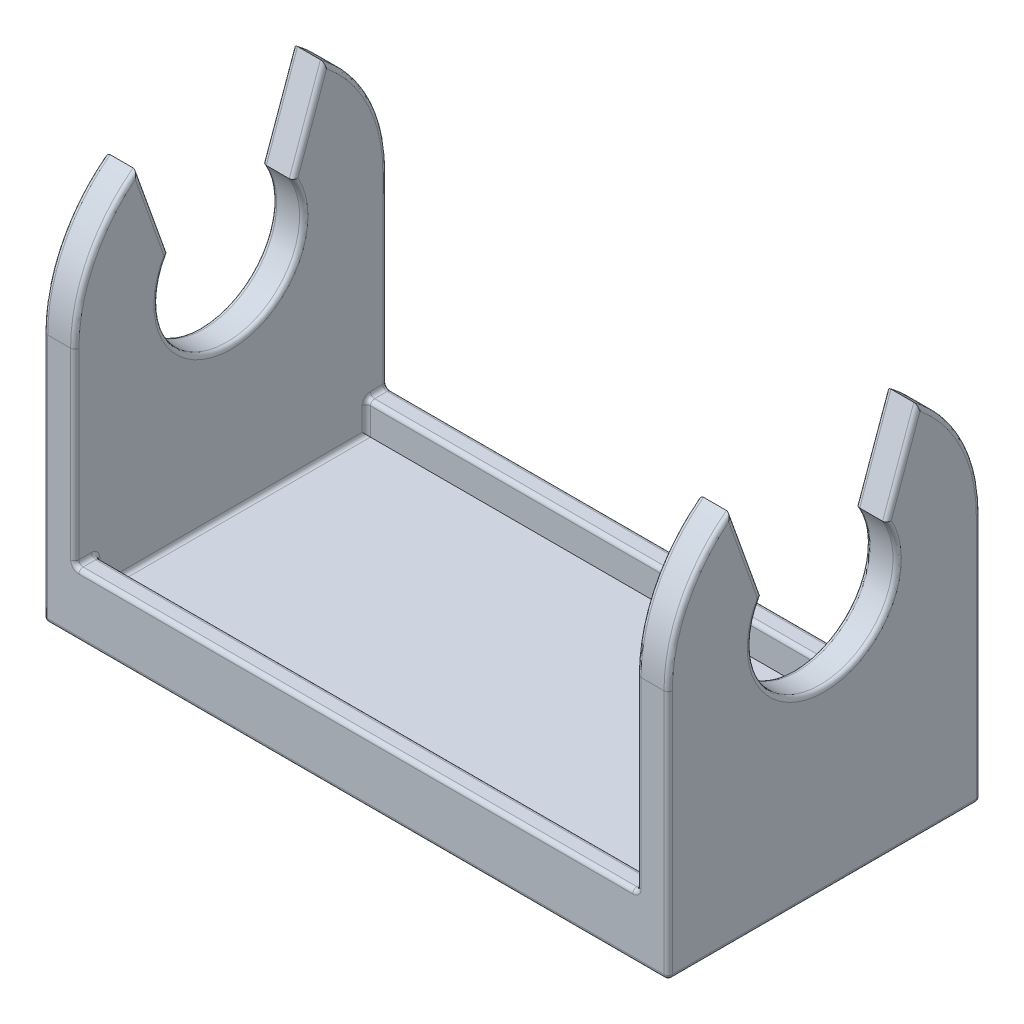
SolidWorks part; units mm, degrees
ref_plane "前视基准面" through (0, 0, 0) normal (0, 0, 1) x (1, 0, 0)
ref_plane "上视基准面" through (0, 0, 0) normal (0, 1, 0) x (1, 0, 0)
ref_plane "右视基准面" through (0, 0, 0) normal (1, 0, 0) x (0, 0, -1)
sketch "草图1" plane through (0, 0, 0) normal (1, 0, 0) x (0, 0, -1)
  line L0 (0, 0) -> (0, 12) construction
  line L1 (7.5, 0) -> (-7.5, 0)
  line L6 (-7.5, 0) -> (-7.5, 12)
  line L7 (0, 12) -> (-3, 12) construction
  line L8 (-3, 12) -> (-3, 13.8028) construction
  line L9 (0, 12) -> (-4.5, 12) construction
  line L10 (-4.5, 12) -> (-4.5, 18) construction
  line L11 (-4.5, 18) -> (-3, 13.8028)
  line L16 (7.5, 0) -> (7.5, 12)
  line L17 (4.5, 18) -> (3, 13.8028)
  arc A0 (-3, 13.8028) -> (3, 13.8028) centre (0, 12) ccw
  arc A1 (-4.5, 18) -> (-7.5, 12) centre (0, 12) ccw
  arc A2 (4.5, 18) -> (7.5, 12) centre (0, 12) cw
  dimension "D2" = 7
  dimension "D8" = 15
  dimension "D1" = 12
  dimension "D3" = 7.5
  dimension "D9" = 3
  dimension "D10" = 4.5
  dimension "D11" = 90
extrude "凸台-拉伸1" add sketch "草图1" along normal blind 30
sketch "草图2" plane through (0, 0, 7.5) normal (0, 0, 1) x (1, 0, 0)
  line L0 (30, 18) -> (0, 18) construction
  line L1 (1.5, 1.5) -> (28.5, 1.5)
  line L2 (1.5, 1.5) -> (1.5, 18)
  line L3 (1.5, 18) -> (28.5, 18)
  line L4 (28.5, 1.5) -> (28.5, 18)
  line L5 (0, 12) -> (0, 0) construction
  line L6 (30, 0) -> (0, 0) construction
  line L7 (30, 12) -> (30, 0) construction
  dimension "D1" = 1.5
  dimension "D2" = 1.5
  dimension "D3" = 1.5
extrude "切除-拉伸1" cut sketch "草图2" against normal up to next
sketch "草图3" plane through (0, 1.5, 0) normal (0, 1, 0) x (1, 0, 0)
  line L0 (28.5, 7.5) -> (28.5, 4.5) construction
  line L1 (1.5, 7.5) -> (28.5, 7.5)
  line L2 (1.5, 7.5) -> (1.5, 6.5)
  line L3 (1.5, 6.5) -> (28.5, 6.5)
  line L4 (28.5, 7.5) -> (28.5, 6.5)
  line L5 (28.5, 7.5) -> (28.5, -7.5) construction
  line L6 (1.5, -7.5) -> (28.5, -7.5)
  line L7 (1.5, -7.5) -> (1.5, -6.5)
  line L8 (1.5, -6.5) -> (28.5, -6.5)
  line L9 (28.5, -7.5) -> (28.5, -6.5)
  dimension "D1" = 1
  dimension "D2" = 1
extrude "凸台-拉伸2" add sketch "草图3" along normal blind 1.5
sketch "草图4" plane through (0, 0, 0) normal (0, 0, 1) x (1, 0, 0)
  line L0 (0, 0) -> (7.5, 0) construction
  line L1 (30, 0) -> (0, 0) construction
  line L2 (7.5, 0) -> (7.5, -2) construction
  line L3 (7.5, -2) -> (7.5, -2.5) construction
  line L4 (6, 0) -> (9, 0)
  line L5 (9, 0) -> (9, -0.6771)
  line L6 (5.55, -2.5) -> (9.45, -2.5)
  line L7 (9.45, -2.5) -> (9.45, -1.5556)
  line L8 (5.55, -2.5) -> (5.55, -1.5556)
  line L9 (6, 0) -> (6, -0.6771)
  arc A0 (9.45, -1.5556) -> (9, -0.6771) centre (7.5, -2) ccw
  arc A1 (5.55, -1.5556) -> (6, -0.6771) centre (7.5, -2) cw
  dimension "D6" = 2
  dimension "D1" = 7.5
  dimension "D2" = 2
  dimension "D3" = 0.5
  dimension "D4" = 1.5
  dimension "D5" = 1.95
extrude "凸台-拉伸3" add sketch "草图4" along normal blind 2 and the other way blind 2
pattern_linear "阵列(线性)1" count 2 spacing 15 along (1, 0, 0) of "凸台-拉伸3"
sketch "草图5" plane through (0, 0, 0) normal (-1, 0, 0) x (0, 0, 1)
  line L0 (0, 0) -> (0, -2) construction
  line L1 (0, -2) -> (0, -2.5) construction
  line L2 (-2, -2.5) -> (2, -2.5) construction
  line L3 (0, 0) -> (1.5, 0) construction
  line L4 (7.5, 0) -> (-7.5, 0) construction
  line L5 (1.5, 0) -> (1.5, -0.6771)
  line L6 (0, -2.5) -> (1.95, -2.5) construction
  line L7 (1.95, -2.5) -> (1.95, -1.5556)
  line L8 (1.95, -2.5) -> (2, -2.5)
  line L9 (2, -2.5) -> (2, 0)
  line L10 (2, 0) -> (1.5, 0)
  line L11 (-2, 0) -> (-1.5, 0)
  line L12 (-2, -2.5) -> (-2, 0)
  line L13 (-1.95, -2.5) -> (-2, -2.5)
  line L14 (-1.95, -2.5) -> (-1.95, -1.5556)
  line L15 (-1.5, 0) -> (-1.5, -0.6771)
  arc A0 (1.95, -1.5556) -> (1.5, -0.6771) centre (0, -2) ccw
  arc A1 (-1.95, -1.5556) -> (-1.5, -0.6771) centre (0, -2) cw
  dimension "D1" = 2
  dimension "D2" = 1.5
  dimension "D3" = 1.95
extrude "切除-拉伸2" cut sketch "草图5" against normal through all
fillet "圆角1" radius 0.2 46 edges at (28.5, 1.5, 0) (28.5, 2.25, -6.5) (28.5, 15.3541, -6.7082) (28.5, 15.9014, -3.75) (28.5, 8.5, 0) (28.5, 15.9014, 3.75) (28.5, 15.3541, 6.7082) (28.5, 2.25, 6.5) (1.5, 15.3541, 6.7082) (1.5, 15.9014, 3.75) (1.5, 8.5, 0) (1.5, 15.9014, -3.75) (1.5, 15.3541, -6.7082) (1.5, 2.25, -6.5) (1.5, 1.5, 0) (1.5, 2.25, 6.5) (28.5, 3, -7) (15, 3, -6.5) (1.5, 3, -7) (15, 3, 6.5) (28.5, 3, 7) (1.5, 3, 7) (15, 0, 7.5) (1.5, 7.5, 7.5) (15, 3, 7.5) (28.5, 7.5, 7.5) (30, 0, 0) (30, 6, 7.5) (30, 15.3541, 6.7082) (30, 15.9014, 3.75) (30, 8.5, 0) (30, 15.9014, -3.75) (30, 15.3541, -6.7082) (15, 0, -7.5) (30, 6, -7.5) (28.5, 7.5, -7.5) (15, 3, -7.5) (1.5, 7.5, -7.5) (0, 15.3541, -6.7082) (0, 15.9014, -3.75) (0, 8.5, 0) (0, 15.9014, 3.75) (0, 15.3541, 6.7082) (0, 6, 7.5) (0, 0, 0) (0, 6, -7.5)
fillet "圆角2" radius 0.1 8 edges at (9.45, -2.5, 0) (7.5, -2.5, -1.95) (5.55, -2.5, 0) (7.5, -2.5, 1.95) (24.45, -2.5, 0) (22.5, -2.5, -1.95) (20.55, -2.5, 0) (22.5, -2.5, 1.95)
